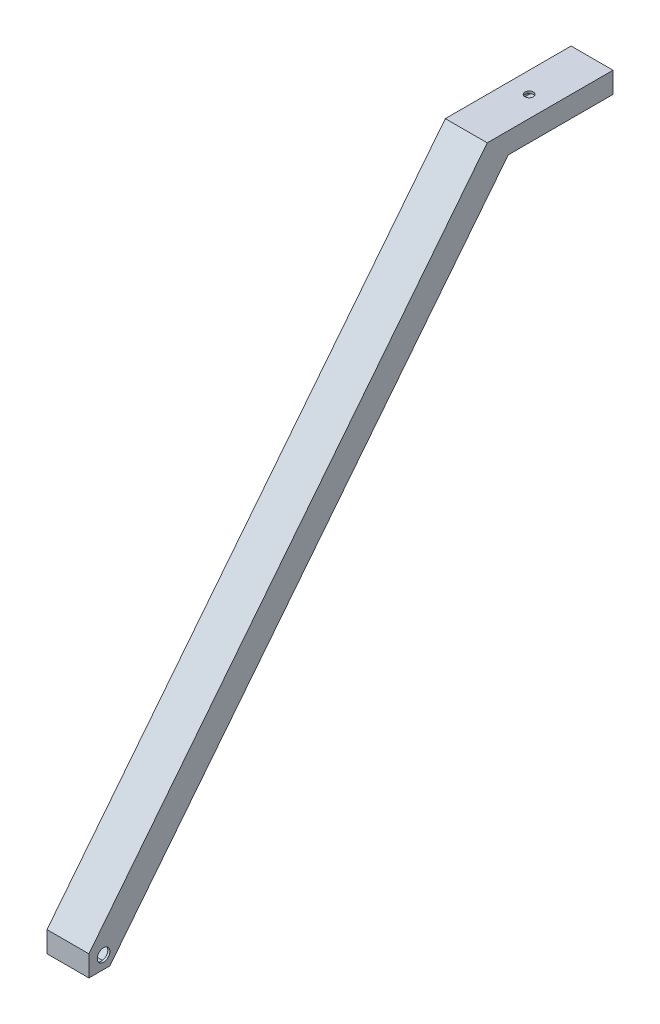
SolidWorks part; units mm, degrees
material "Hexcel AS4C (3000 Filaments)"
ref_plane "Ön Düzlem" through (0, 0, 0) normal (0, 0, 1) x (1, 0, 0)
ref_plane "Üst Düzlem" through (0, 0, 0) normal (0, 1, 0) x (1, 0, 0)
ref_plane "Sağ Düzlem" through (0, 0, 0) normal (1, 0, 0) x (0, 0, -1)
sketch "Çizim1" plane through (0, 0, 0) normal (1, 0, 0) x (0, 0, -1)
  line L0 (0, 0) -> (-50, 0)
  line L1 (-50, 0) -> (-240, -240)
  line L3 (-250, -230) -> (-60, 10)
  line L4 (-60, 10) -> (0, 10)
  line L5 (0, 10) -> (0, 0)
  line L6 (-250, -230) -> (-250, -240)
  line L7 (-250, -240) -> (-240, -240)
  dimension "D1" = 60
  dimension "D2" = 50
  dimension "D3" = 10
  dimension "D4" = 10
  dimension "D5" = 250
  dimension "D6" = 10
  dimension "D7" = 190
extrude "Yükseklik-Ekstrüzyon1" add sketch "Çizim1" along normal mid plane 20
shell "İç Boşaltma1" thickness 1
sketch "Çizim2" plane through (0, 10, 0) normal (0, 1, 0) x (1, 0, 0)
  circle A0 centre (0, -30) radius 2
  dimension "D1" = 4
  dimension "D2" = 30
extrude "Kes-Ekstrüzyon1" cut sketch "Çizim2" against normal blind 27
sketch "Çizim3" plane through (-10, 0, 0) normal (-1, 0, 0) x (0, 0, 1)
  line L0 (250, -230) -> (250, -240) construction
  line L1 (250, -240) -> (240, -240) construction
  circle A0 centre (243, -234) radius 3
  dimension "D1" = 6
  dimension "D2" = 7
  dimension "D3" = 6
extrude "Kes-Ekstrüzyon2" cut sketch "Çizim3" against normal blind 37
